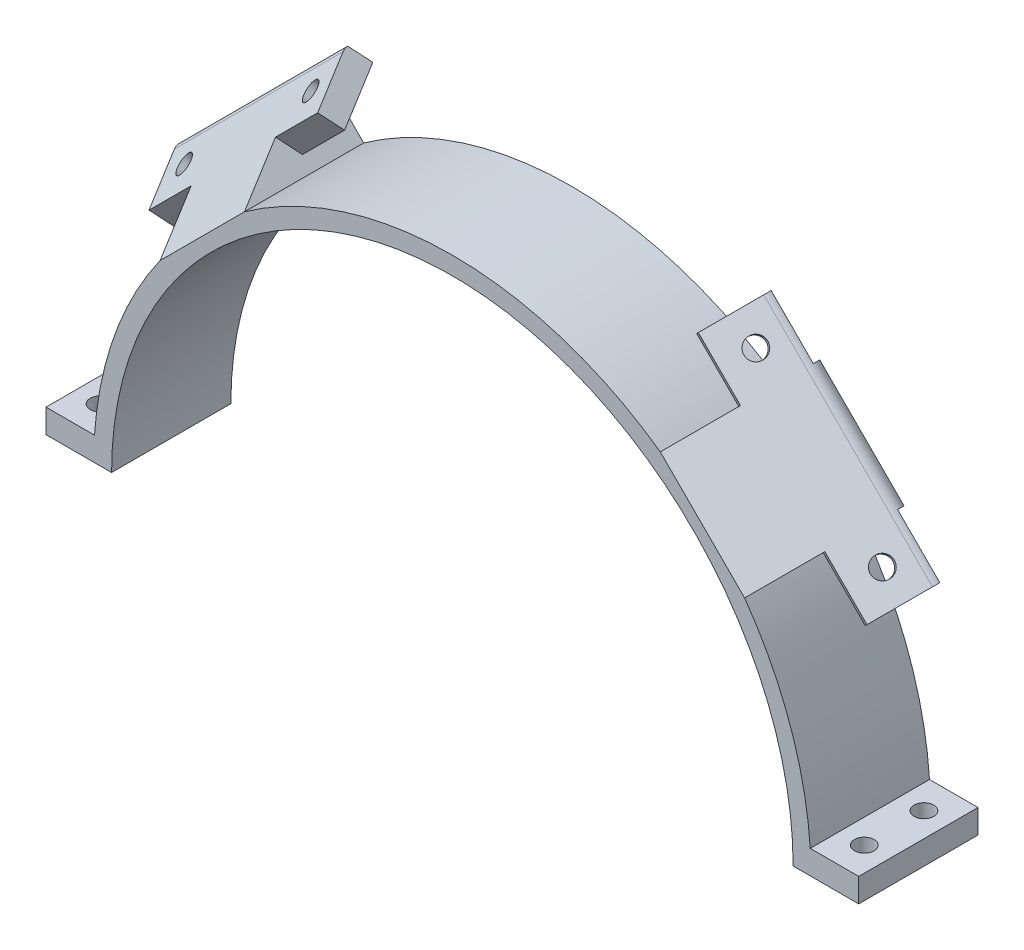
SolidWorks part; units mm, degrees
material "ABS"
ref_plane "正面" through (0, 0, 0) normal (0, 0, 1) x (1, 0, 0)
ref_plane "平面" through (0, 0, 0) normal (0, 1, 0) x (1, 0, 0)
ref_plane "右側面" through (0, 0, 0) normal (1, 0, 0) x (0, 0, -1)
sketch "ｽｹｯﾁ1" plane through (0, 0, 0) normal (0, 0, 1) x (1, 0, 0)
  line L0 (-57.15, 0) -> (57.15, 0) construction
  line L1 (-57.15, 0) -> (-60.15, 0)
  line L2 (57.15, 0) -> (60.15, 0)
  arc A0 (-57.15, 0) -> (57.15, 0) centre (0, 0) cw
  arc A1 (-60.15, 0) -> (60.15, 0) centre (0, 0) cw
  dimension "D1" = 114.3
  dimension "D2" = 3
extrude "ﾎﾞｽ - 押し出し1" add sketch "ｽｹｯﾁ1" along normal blind 20
sketch "ｽｹｯﾁ3" plane through (0, 0, 20) normal (0, 0, 1) x (1, 0, 0)
  line L0 (0, 0) -> (-42.5325, 42.5325) construction
  line L1 (-60.15, 0) -> (-57.15, 0) construction
  line L2 (-41.9406, 41.9406) -> (-34.8695, 49.0116)
  line L3 (-34.8695, 49.0116) -> (-43.7083, 57.8505)
  line L4 (-43.7083, 57.8505) -> (-57.8505, 43.7083)
  line L5 (-57.8505, 43.7083) -> (-49.0116, 34.8695)
  line L6 (-49.0116, 34.8695) -> (-41.9406, 41.9406)
  line L7 (0, 0) -> (0, 60.15) construction
  line L8 (57.8505, 43.7083) -> (49.0116, 34.8695)
  line L9 (43.7083, 57.8505) -> (57.8505, 43.7083)
  line L10 (34.8695, 49.0116) -> (43.7083, 57.8505)
  line L11 (41.9406, 41.9406) -> (34.8695, 49.0116)
  line L12 (49.0116, 34.8695) -> (41.9406, 41.9406)
  arc A0 (60.15, 0) -> (-60.15, 0) centre (0, 0) ccw construction
  dimension "D1" = 45
  dimension "D2" = 20
  dimension "D3" = 12.5
extrude "ﾎﾞｽ - 押し出し2" add sketch "ｽｹｯﾁ3" against normal up to surface (20 mm away) up to face at (0, 29.325, 0)
sketch "ｽｹｯﾁ4" plane through (-7.0711, -7.0711, 0) normal (-0.7071, -0.7071, 0) x (0, 0, 1)
  line L0 (0, 71.8129) -> (20, 59.3129)
  line L1 (20, 59.3129) -> (20, 71.8129)
  line L2 (20, 71.8129) -> (0, 71.8129)
extrude "ｶｯﾄ - 押し出し1" cut sketch "ｽｹｯﾁ4" against normal up to next
sketch "ｽｹｯﾁ5" plane through (7.0711, -7.0711, 0) normal (0.7071, -0.7071, 0) x (0, 0, -1)
  line L0 (0, 71.8129) -> (-20, 59.3129)
  line L1 (-20, 59.3129) -> (-20, 71.8129)
  line L2 (-20, 71.8129) -> (0, 71.8129)
extrude "ｶｯﾄ - 押し出し2" cut sketch "ｽｹｯﾁ5" against normal up to next
sketch "ｽｹｯﾁ6" plane through (-36.5155, 36.5155, 32.2755) normal (-0.5996, 0.5996, 0.53) x (0.7992, 0.4135, 0.4363)
  line L0 (-19.5821, 32.6368) -> (-7.4477, 12.4129) construction
  line L1 (-11.0072, 37.7818) -> (-28.157, 27.4919) construction
  line L2 (1.1272, 17.5579) -> (-16.0227, 7.268) construction
  line L3 (-4.94, 27.6698) -> (-22.0899, 17.3799) construction
  line L4 (-11.0072, 37.7818) -> (1.1272, 17.5579) construction
  line L5 (-28.157, 27.4919) -> (-16.0227, 7.268) construction
  line L6 (-26.8271, 25.2753) -> (-35.402, 20.1303)
  line L7 (-24.7485, 21.811) -> (-16.0227, 7.268) construction
  line L8 (-35.402, 20.1303) -> (-30.2571, 11.5554)
  line L9 (-30.2571, 11.5554) -> (-21.6821, 16.7004)
  line L10 (-21.6821, 16.7004) -> (-26.8271, 25.2753)
  line L11 (4.0427, 32.1352) -> (-4.5323, 26.9903)
  line L12 (-1.1023, 40.7102) -> (4.0427, 32.1352)
  line L13 (-9.6772, 35.5652) -> (-1.1023, 40.7102)
  line L14 (-4.5323, 26.9903) -> (-9.6772, 35.5652)
  dimension "D1" = 10
  dimension "D2" = 10
  dimension "D3" = 11
extrude "ﾎﾞｽ - 押し出し3" add sketch "ｽｹｯﾁ6" against normal blind 4
sketch "ｽｹｯﾁ7" plane through (36.5155, 36.5155, 32.2755) normal (0.5996, 0.5996, 0.53) x (0.7992, -0.4135, -0.4363)
  line L0 (19.5821, 32.6368) -> (7.4477, 12.4129) construction
  line L1 (28.157, 27.4919) -> (11.0072, 37.7818) construction
  line L2 (-1.1272, 17.5579) -> (16.0227, 7.268) construction
  line L3 (9.6772, 35.5652) -> (4.5323, 26.9903)
  line L4 (-1.1272, 17.5579) -> (11.0072, 37.7818) construction
  line L5 (7.5986, 32.1009) -> (-1.1272, 17.5579) construction
  line L6 (4.5323, 26.9903) -> (-4.0427, 32.1352)
  line L7 (-4.0427, 32.1352) -> (1.1023, 40.7102)
  line L8 (1.1023, 40.7102) -> (9.6772, 35.5652)
  line L9 (30.2571, 11.5554) -> (35.402, 20.1303)
  line L10 (21.6821, 16.7004) -> (30.2571, 11.5554)
  line L11 (26.8271, 25.2753) -> (21.6821, 16.7004)
  line L12 (35.402, 20.1303) -> (26.8271, 25.2753)
  dimension "D1" = 10
  dimension "D2" = 10
  dimension "D3" = 11
extrude "ﾎﾞｽ - 押し出し4" add sketch "ｽｹｯﾁ7" against normal blind 4
sketch "ｽｹｯﾁ8" plane through (36.5155, 36.5155, 32.2755) normal (0.5996, 0.5996, 0.53) x (0.7992, -0.4135, -0.4363)
  line L0 (-1.4702, 36.4227) -> (32.8295, 15.8429) construction
  line L1 (1.1023, 40.7102) -> (-4.0427, 32.1352) construction
  line L2 (30.2571, 11.5554) -> (35.402, 20.1303) construction
  circle A0 centre (2.8173, 33.8502) radius 1.65
  circle A1 centre (28.5421, 18.4154) radius 1.65
  dimension "D1" = 3.3
  dimension "D3" = 5
  dimension "D2" = 5
extrude "ｶｯﾄ - 押し出し3" cut sketch "ｽｹｯﾁ8" against normal up to next
sketch "ｽｹｯﾁ9" plane through (-36.5155, 36.5155, 32.2755) normal (-0.5996, 0.5996, 0.53) x (0.7992, 0.4135, 0.4363)
  line L0 (1.4702, 36.4227) -> (-32.8295, 15.8429) construction
  line L1 (4.0427, 32.1352) -> (-1.1023, 40.7102) construction
  line L2 (-35.402, 20.1303) -> (-30.2571, 11.5554) construction
  circle A0 centre (-2.8173, 33.8502) radius 1.65
  circle A1 centre (-28.5421, 18.4154) radius 1.65
  dimension "D1" = 3.3
  dimension "D3" = 5
  dimension "D2" = 5
fillet "ﾌｨﾚｯﾄ1" radius 2 2 edges at (50.7794, 50.7794, 0) (-50.7794, 50.7794, 0)
extrude "ｶｯﾄ - 押し出し4" cut sketch "ｽｹｯﾁ9" against normal up to next
sketch "ｽｹｯﾁ10" plane through (0, 0, 0) normal (0, -1, 0) x (1, 0, 0)
  line L0 (0, 0) -> (0, 20) construction
  line L1 (-57.15, 0) -> (57.15, 0) construction
  line L2 (57.15, 20) -> (-57.15, 20) construction
  line L3 (-58.15, 20) -> (-68.15, 20)
  line L4 (-68.15, 20) -> (-68.15, 0)
  line L5 (-68.15, 0) -> (-58.15, 0)
  line L6 (-58.15, 20) -> (-58.15, 0)
  line L7 (58.15, 20) -> (68.15, 20)
  line L8 (68.15, 20) -> (68.15, 0)
  line L9 (68.15, 0) -> (58.15, 0)
  line L10 (58.15, 20) -> (58.15, 0)
  line L11 (-60.15, 20) -> (-57.15, 20) construction
  line L12 (-60.15, 0) -> (-57.15, 0) construction
  line L13 (-60.15, 20) -> (-60.15, 0) construction
  dimension "D1" = 10
  dimension "D2" = 2
extrude "ﾎﾞｽ - 押し出し5" add sketch "ｽｹｯﾁ10" against normal blind 4
sketch "ｽｹｯﾁ11" plane through (0, 4, 0) normal (0, 1, 0) x (1, 0, 0)
  line L0 (64.0834, 0) -> (64.0834, -20) construction
  line L1 (60.0169, 0) -> (68.15, 0) construction
  line L2 (68.15, -20) -> (60.0169, -20) construction
  line L3 (0, 0) -> (0, -20) construction
  line L4 (-34.8695, -20) -> (34.8695, -20) construction
  circle A0 centre (64.0834, -5) radius 1.65
  circle A1 centre (64.0834, -15) radius 1.65
  circle A2 centre (-64.0834, -15) radius 1.65
  circle A3 centre (-64.0834, -5) radius 1.65
  dimension "D1" = 3.3
  dimension "D2" = 5
  dimension "D3" = 5
extrude "ｶｯﾄ - 押し出し5" cut sketch "ｽｹｯﾁ11" against normal up to next
